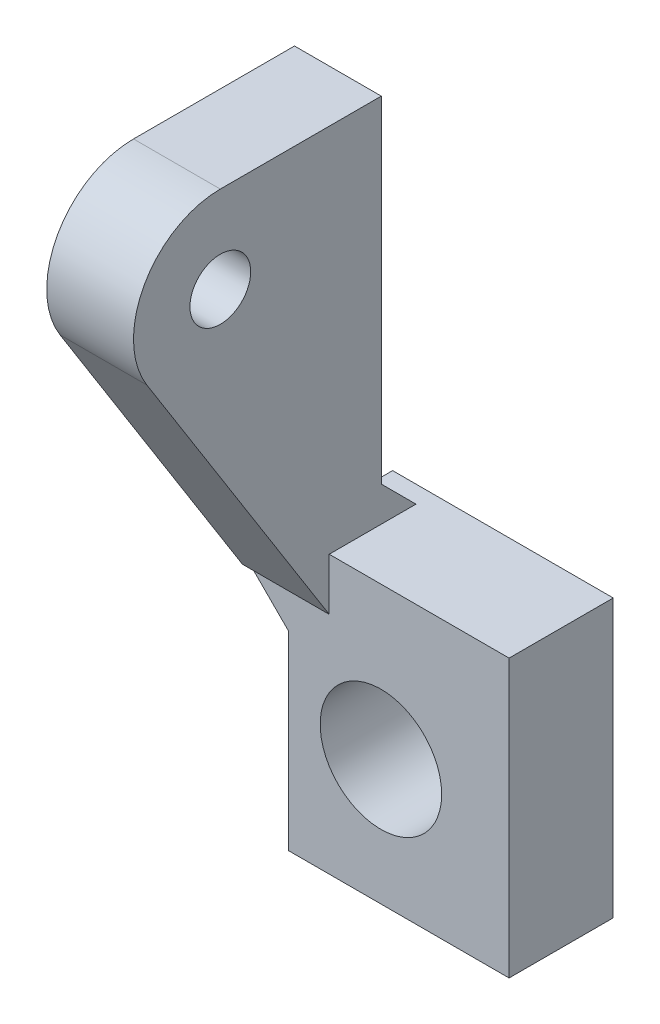
SolidWorks part; units mm, degrees
ref_plane "Front Plane" through (0, 0, 0) normal (0, 0, 1) x (1, 0, 0)
ref_plane "Top Plane" through (0, 0, 0) normal (0, 1, 0) x (1, 0, 0)
ref_plane "Right Plane" through (0, 0, 0) normal (1, 0, 0) x (0, 0, -1)
sketch "Sketch1" plane through (0, 0, 46.4115) normal (0, 0, 1) x (1, 0, 0)
  line L5 (33.1528, -0.655) -> (45.8638, -0.655)
  line L6 (33.1528, -0.655) -> (33.1528, 15.3086)
  line L7 (33.1528, 15.3086) -> (45.8638, 15.3086)
  line L8 (45.8638, -0.655) -> (45.8638, 15.3086)
  circle A0 centre (38.4789, 6.5666) radius 1.8 construction
  circle A1 centre (38.4789, 6.5666) radius 1.8
extrude "Boss-Extrude1" add sketch "Sketch1" along normal blind 1
sketch "Sketch2" plane through (30.5, 0, 0) normal (1, 0, 0) x (0, 0, -1)
  line L1 (-58.6878, 36.6687) -> (-49.4115, 36.6687)
  line L2 (-49.4115, 36.6687) -> (-49.4115, 17.3086)
  line L3 (-49.4115, 17.3086) -> (-47.4115, 15.3086)
  line L4 (-47.4115, 15.3086) -> (-47.4115, 12.3086)
  line L5 (-47.4115, -0.655) -> (-47.4115, 15.3086) construction
  line L6 (-47.4115, 12.3086) -> (-52.4115, 12.3086)
  line L7 (-52.4115, 12.3086) -> (-62.9195, 29.0055)
  arc A0 (-58.6878, 36.6687) -> (-62.9195, 29.0055) centre (-58.6878, 31.6687) ccw
  circle A1 centre (-58.6878, 31.6687) radius 1.75
  dimension "D1" = 10
  dimension "D2" = 45
  dimension "D3" = 2
  dimension "D4" = 5
  dimension "D5" = 3
extrude "Boss-Extrude2" add sketch "Sketch2" along normal blind 5
sketch "Sketch3" plane through (0, 0, 47.4115) normal (0, 0, 1) x (1, 0, 0)
  line L6 (35.5, 15.3086) -> (35.5, 12.3086)
  line L7 (35.5, 12.3086) -> (33.1528, 12.3086)
  line L8 (33.1528, 12.3086) -> (33.1528, -0.655)
  line L9 (33.1528, -0.655) -> (45.8638, -0.655)
  line L10 (45.8638, -0.655) -> (45.8638, 15.3086)
  line L11 (45.8638, 15.3086) -> (35.5, 15.3086)
  line L12 (35.5, 15.3086) -> (35.5, 12.3086)
  line L13 (35.5, 12.3086) -> (33.1528, 12.3086)
  line L14 (33.1528, 12.3086) -> (33.1528, -0.655)
  line L15 (33.1528, -0.655) -> (45.8638, -0.655)
  line L16 (45.8638, -0.655) -> (45.8638, 15.3086)
  line L17 (45.8638, 15.3086) -> (35.5, 15.3086)
  circle A0 centre (38.4789, 6.5666) radius 3.5
  dimension "D1" = 7
  dimension "D2" = 0
extrude "Boss-Extrude3" add sketch "Sketch3" along normal blind 5
chamfer "Chamfer1" distance 2 angle 45 1 edges at (33.1528, 12.3086, 49.9115)
